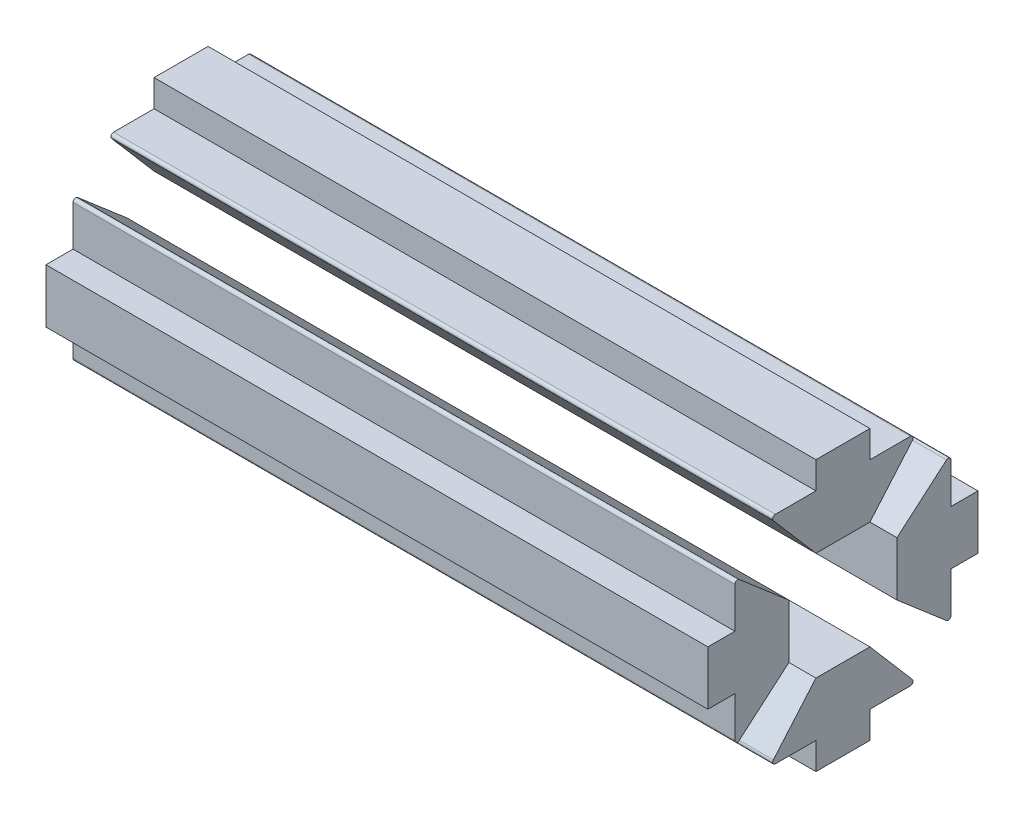
SolidWorks part; units mm, degrees
ref_plane "Front Plane" through (0, 0, 0) normal (0, 0, 1) x (1, 0, 0)
ref_plane "Top Plane" through (0, 0, 0) normal (0, 1, 0) x (1, 0, 0)
ref_plane "Right Plane" through (0, 0, 0) normal (1, 0, 0) x (0, 0, -1)
sketch "Sketch1" plane through (0, 0, 0) normal (0, 1, 0) x (1, 0, 0)
  line L1 (38.1, -25.4) -> (-38.1, -25.4)
  line L2 (38.1, -25.4) -> (38.1, 25.4)
  line L3 (38.1, 25.4) -> (-38.1, 25.4)
  line L4 (-38.1, -25.4) -> (-38.1, 25.4)
  line L5 (38.1, -25.4) -> (-38.1, 25.4) construction
  line L6 (38.1, 25.4) -> (-38.1, -25.4) construction
  point P0 (0, 0)
  dimension "D1" = 76.2
  dimension "D2" = 50.8
sketch "Sketch10" plane through (0, 0, 0) normal (1, 0, 0) x (0, 0, -1)
  line L0 (-12.7, 0) -> (0, 0) construction
  line L1 (0, 0) -> (0, -12.7) construction
  line L2 (0, 0) -> (0, 12.7) construction
  line L3 (0, 0) -> (12.7, 0) construction
  line L4 (6.35, 10.16) -> (-6.35, 10.16)
  line L5 (-6.5427, 9.7405) -> (-2.54, 5.08)
  line L6 (6.5427, 9.7405) -> (2.54, 5.08)
  line L7 (2.54, 5.08) -> (-2.54, 5.08)
  line L8 (-5.08, -2.54) -> (-5.08, 2.54)
  line L9 (-5.08, 2.54) -> (-9.7405, 6.5427)
  line L10 (-10.16, -6.35) -> (-10.16, 6.35)
  line L11 (-9.7405, -6.5427) -> (-5.08, -2.54)
  line L12 (-12.7, -2.54) -> (-12.7, 2.54)
  line L13 (-12.7, 2.54) -> (-10.16, 2.54)
  line L14 (-10.16, 2.54) -> (-10.16, -2.54)
  line L15 (-10.16, -2.54) -> (-12.7, -2.54)
  line L16 (2.54, 12.7) -> (-2.54, 12.7)
  line L17 (-2.54, 12.7) -> (-2.54, 10.16)
  line L18 (-2.54, 10.16) -> (2.54, 10.16)
  line L19 (2.54, 10.16) -> (2.54, 12.7)
  line L20 (2.54, -12.7) -> (-2.54, -12.7)
  line L21 (2.54, -5.08) -> (-2.54, -5.08)
  line L23 (6.35, -10.16) -> (-6.35, -10.16)
  line L24 (-2.54, -12.7) -> (-2.54, -10.16)
  line L26 (2.54, -12.7) -> (2.54, -10.16)
  line L27 (-2.54, -10.16) -> (2.54, -10.16)
  line L28 (-2.54, -5.08) -> (-6.5427, -9.7405)
  line L29 (2.54, -5.08) -> (6.5427, -9.7405)
  line L30 (5.08, -2.54) -> (5.08, 2.54)
  line L31 (12.7, -2.54) -> (12.7, 2.54)
  line L32 (12.7, 2.54) -> (10.16, 2.54)
  line L33 (10.16, 2.54) -> (10.16, -2.54)
  line L34 (10.16, -2.54) -> (12.7, -2.54)
  line L35 (10.16, -6.35) -> (10.16, 6.35)
  line L36 (5.08, 2.54) -> (9.7405, 6.5427)
  line L37 (5.08, -2.54) -> (9.7405, -6.5427)
  arc A0 (-10.16, -6.35) -> (-9.7405, -6.5427) centre (-9.906, -6.35) ccw
  arc A1 (-9.7405, 6.5427) -> (-10.16, 6.35) centre (-9.906, 6.35) ccw
  arc A2 (6.35, 10.16) -> (6.5427, 9.7405) centre (6.35, 9.906) cw
  arc A3 (-6.35, 10.16) -> (-6.5427, 9.7405) centre (-6.35, 9.906) ccw
  arc A4 (-6.35, -10.16) -> (-6.5427, -9.7405) centre (-6.35, -9.906) cw
  arc A6 (6.5427, -9.7405) -> (6.35, -10.16) centre (6.35, -9.906) cw
  arc A8 (9.7405, -6.5427) -> (10.16, -6.35) centre (9.906, -6.35) ccw
  arc A9 (10.16, 6.35) -> (9.7405, 6.5427) centre (9.906, 6.35) ccw
  point P4 (0, 5.08)
  point P10 (0, 10.16)
  point P17 (-5.08, 0)
  point P20 (-10.16, 0)
  point P30 (-12.7, 0)
  point P35 (0, 12.7)
  point P39 (0, -12.7)
  point P42 (0, -5.08)
  point P46 (0, -10.16)
  point P52 (5.08, 0)
  point P55 (12.7, 0)
  point P60 (10.16, 0)
  dimension "D1" = 0.254
  dimension "D16" = 0.254
  dimension "D2" = 5.08
  dimension "D3" = 5.08
  dimension "D4" = 2.54
  dimension "D5" = 2.54
  dimension "D6" = 5.08
  dimension "D7" = 12.7
  dimension "D8" = 5.08
  dimension "D9" = 12.7
  dimension "D10" = 5.08
  dimension "D11" = 5.08
  dimension "D12" = 12.7
  dimension "D13" = 5.08
  dimension "D14" = 5.08
  dimension "D15" = 2.54
extrude "Boss-Extrude3" add sketch "Sketch10" against normal blind 62.23 separate body
